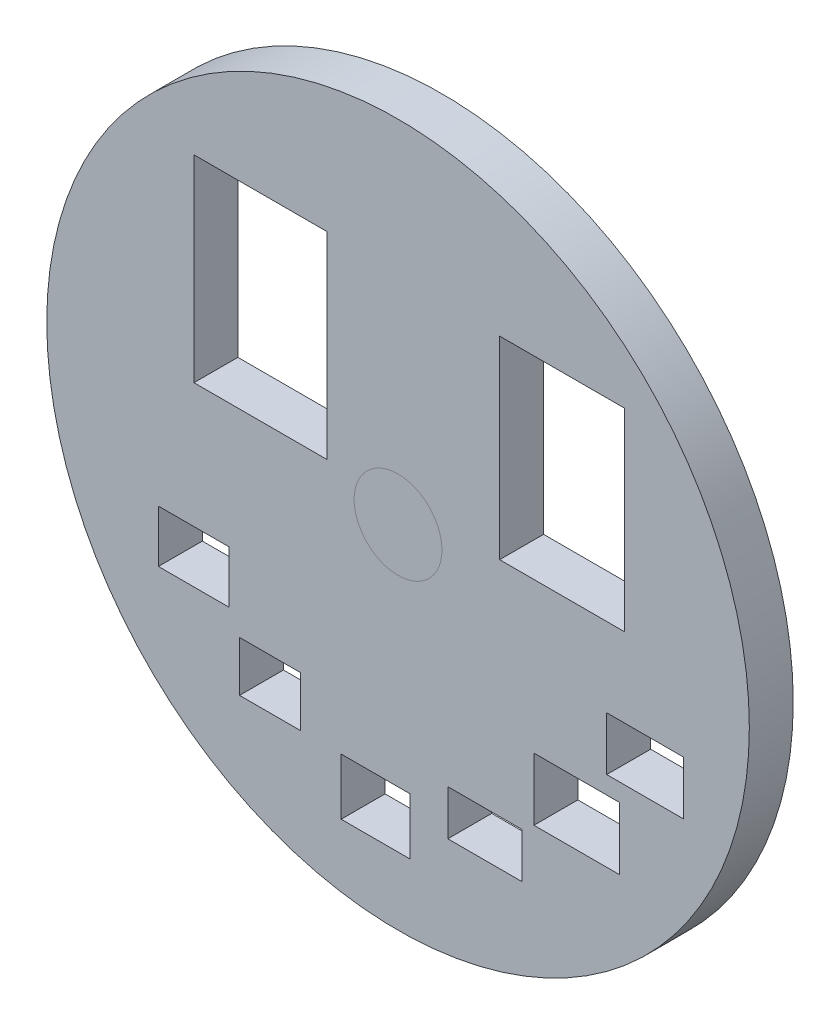
SolidWorks part; units mm, degrees
material "6061 Alloy"
ref_plane "Front Plane" through (0, 0, 0) normal (0, 0, 1) x (1, 0, 0)
ref_plane "Top Plane" through (0, 0, 0) normal (0, 1, 0) x (1, 0, 0)
ref_plane "Right Plane" through (0, 0, 0) normal (1, 0, 0) x (0, 0, -1)
sketch "Sketch1" plane through (0, 0, 0) normal (0, 0, 1) x (1, 0, 0)
  circle A0 centre (0, 0) radius 50.8
  dimension "D1" = 101.6
extrude "Boss-Extrude1" add sketch "Sketch1" along normal blind 6.35
sketch "Sketch2" plane through (0, 0, 6.35) normal (0, 0, 1) x (1, 0, 0)
  line L1 (-29.5115, 31.5676) -> (-10.2806, 31.5676)
  line L2 (-29.5115, 31.5676) -> (-29.5115, 3.0237)
  line L3 (-29.5115, 3.0237) -> (-10.2806, 3.0237)
  line L4 (-10.2806, 31.5676) -> (-10.2806, 3.0237)
  line L5 (14.6953, 30.9629) -> (32.7771, 30.9629)
  line L6 (14.6953, 30.9629) -> (14.6953, 2.9632)
  line L7 (14.6953, 2.9632) -> (32.7771, 2.9632)
  line L8 (32.7771, 30.9629) -> (32.7771, 2.9632)
  line L9 (-34.6518, -14.9976) -> (-24.4317, -14.9976)
  line L10 (-34.6518, -14.9976) -> (-34.6518, -22.5569)
  line L11 (-34.6518, -22.5569) -> (-24.4317, -22.5569)
  line L12 (-24.4317, -14.9976) -> (-24.4317, -22.5569)
  line L13 (-22.9198, -25.5807) -> (-14.0905, -25.5807)
  line L14 (-22.9198, -25.5807) -> (-22.9198, -32.8376)
  line L15 (-22.9198, -32.8376) -> (-14.0905, -32.8376)
  line L16 (-14.0905, -25.5807) -> (-14.0905, -32.8376)
  line L17 (-8.2245, -32.8376) -> (1.7538, -32.8376)
  line L18 (-8.2245, -32.8376) -> (-8.2245, -41.0016)
  line L19 (-8.2245, -41.0016) -> (1.7538, -41.0016)
  line L20 (1.7538, -32.8376) -> (1.7538, -41.0016)
  line L21 (7.1965, -29.2091) -> (17.9004, -29.2091)
  line L22 (7.1965, -29.2091) -> (7.1965, -35.7404)
  line L23 (7.1965, -35.7404) -> (17.9004, -35.7404)
  line L24 (17.9004, -29.2091) -> (17.9004, -35.7404)
  line L25 (19.6542, -18.7773) -> (31.9909, -18.7773)
  line L26 (19.6542, -18.7773) -> (19.6542, -27.8182)
  line L27 (19.6542, -27.8182) -> (31.9909, -27.8182)
  line L28 (31.9909, -18.7773) -> (31.9909, -27.8182)
  line L29 (30.1767, -8.4664) -> (41.304, -8.4664)
  line L30 (30.1767, -8.4664) -> (30.1767, -16.2071)
  line L31 (30.1767, -16.2071) -> (41.304, -16.2071)
  line L32 (41.304, -8.4664) -> (41.304, -16.2071)
  point P32 (-32.7771, 2.8423)
  point P33 (0, 0)
  point P34 (28.3625, 3.3866)
extrude "Cut-Extrude1" cut sketch "Sketch2" against normal through all
sketch "Sketch4" plane through (0, 0, 6.35) normal (0, 0, 1) x (1, 0, 0)
  circle A0 centre (0, 0) radius 6.35
sketch "Sketch5" plane through (0, 0, 6.35) normal (0, 0, 1) x (1, 0, 0)
  circle A0 centre (0, 0) radius 6.35
sketch "Sketch6" plane through (0, 0, 6.35) normal (0, 0, 1) x (1, 0, 0)
  circle A0 centre (0, 0) radius 6.35
split line "Split Line1"
